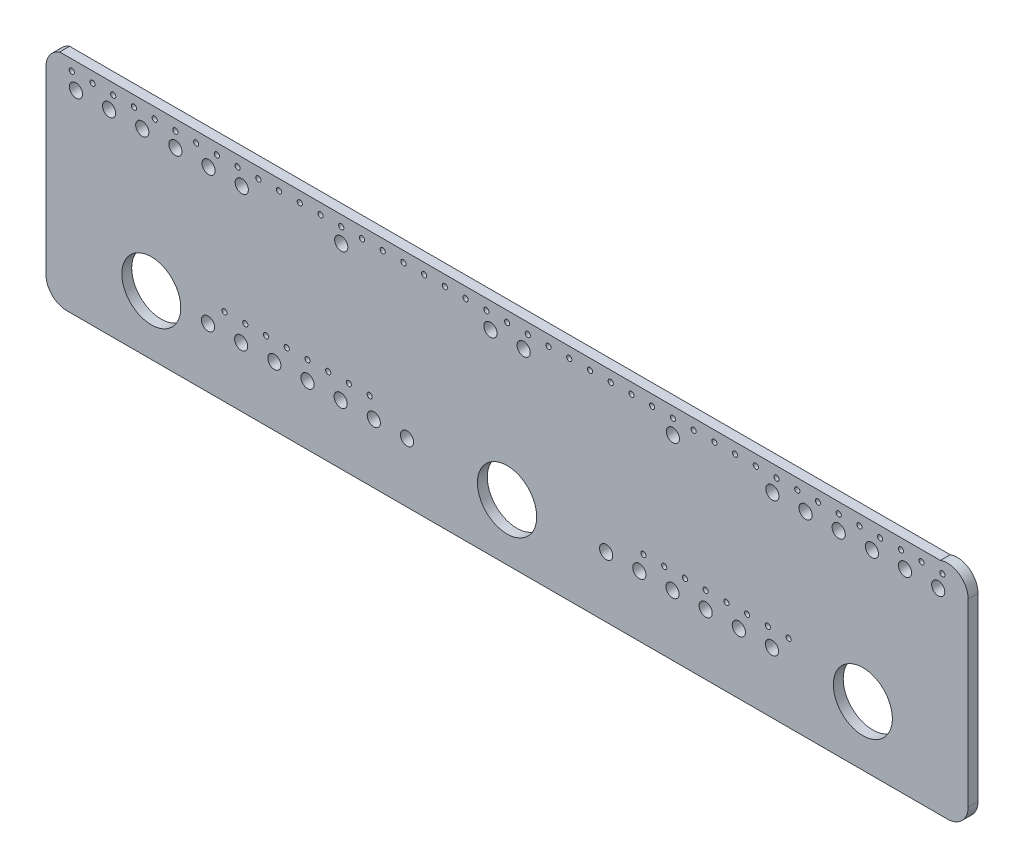
SolidWorks part; units mm, degrees
ref_plane "Front" through (0, 0, 0) normal (0, 0, 1) x (1, 0, 0)
ref_plane "Top" through (0, 0, 0) normal (0, 1, 0) x (1, 0, 0)
ref_plane "Right" through (0, 0, 0) normal (1, 0, 0) x (0, 0, -1)
sketch "Sketch1" plane through (0, 0, 0) normal (0, 0, 1) x (1, 0, 0)
  line L0 (-438.5452, 90.4904) -> (-13.6652, 90.4904)
  line L2 (-445.1498, 81.0845) -> (-445.1498, -5.9096)
  line L4 (-0.2698, 81.0845) -> (-0.2698, -5.9096)
  line L5 (-10.2698, -15.9096) -> (-435.1498, -15.9096)
  circle A0 centre (-394.3498, 12.7904) radius 14.225
  circle A1 centre (-51.0698, 12.7904) radius 14.225
  circle A11 centre (-222.7098, 11.2904) radius 14.3
  arc A26 (-438.5452, 90.4904) -> (-445.1498, 81.0845) centre (-435.1498, 81.0845) ccw
  arc A27 (-13.6652, 90.4904) -> (-0.2698, 81.0845) centre (-10.2698, 81.0845) cw
  circle A54 centre (-174.8998, 13.3845) radius 3.18
  circle A151 centre (-366.9908, 12.7904) radius 3.18
  circle A155 centre (-358.9957, 21.7191) radius 1.25
  circle A159 centre (-94.8998, 13.3845) radius 3.18
  circle A279 centre (-96.8998, 21.3845) radius 1.25
  circle A285 centre (-106.8998, 21.3845) radius 1.25
  circle A286 centre (-350.9908, 12.7904) radius 3.18
  circle A288 centre (-334.9908, 12.7904) radius 3.18
  circle A290 centre (-318.9908, 12.7904) radius 3.18
  circle A292 centre (-302.9908, 12.7904) radius 3.18
  circle A294 centre (-286.9908, 12.7904) radius 3.18
  circle A296 centre (-158.8998, 13.3845) radius 3.18
  circle A297 centre (-142.8998, 13.3845) radius 3.18
  circle A298 centre (-126.8998, 13.3845) radius 3.18
  circle A299 centre (-110.8998, 13.3845) radius 3.18
  circle A309 centre (-86.8998, 21.3845) radius 1.25
  circle A314 centre (-270.9908, 12.7904) radius 3.18
  circle A328 centre (-348.9957, 21.7191) radius 1.25
  circle A361 centre (-116.8998, 21.3845) radius 1.25
  circle A362 centre (-338.9957, 21.7191) radius 1.25
  circle A363 centre (-328.9957, 21.7191) radius 1.25
  circle A364 centre (-318.9957, 21.7191) radius 1.25
  circle A365 centre (-308.9957, 21.7191) radius 1.25
  circle A366 centre (-298.9957, 21.7191) radius 1.25
  circle A367 centre (-288.9957, 21.7191) radius 1.25
  circle A378 centre (-126.8998, 21.3845) radius 1.25
  circle A379 centre (-136.8998, 21.3845) radius 1.25
  circle A380 centre (-146.8998, 21.3845) radius 1.25
  circle A381 centre (-156.8998, 21.3845) radius 1.25
  circle A402 centre (-222.7098, 85.3845) radius 1.25
  circle A438 centre (-142.7098, 78.3345) radius 3.18
  circle A439 centre (-94.7098, 78.3345) radius 3.18
  circle A440 centre (-78.7098, 78.3345) radius 3.18
  circle A441 centre (-30.7098, 78.3345) radius 3.18
  circle A442 centre (-14.7098, 78.3345) radius 3.18
  circle A444 centre (-302.7098, 78.3345) radius 3.18
  circle A445 centre (-350.7098, 78.3345) radius 3.18
  circle A446 centre (-366.7098, 78.3345) radius 3.18
  circle A447 centre (-414.7098, 78.3345) radius 3.18
  circle A448 centre (-212.7098, 85.3845) radius 1.25
  circle A449 centre (-202.7098, 85.3845) radius 1.25
  circle A450 centre (-192.7098, 85.3845) radius 1.25
  circle A451 centre (-182.7098, 85.3845) radius 1.25
  circle A452 centre (-172.7098, 85.3845) radius 1.25
  circle A453 centre (-162.7098, 85.3845) radius 1.25
  circle A454 centre (-152.7098, 85.3845) radius 1.25
  circle A455 centre (-142.7098, 85.3845) radius 1.25
  circle A456 centre (-132.7098, 85.3845) radius 1.25
  circle A457 centre (-122.7098, 85.3845) radius 1.25
  circle A458 centre (-112.7098, 85.3845) radius 1.25
  circle A459 centre (-102.7098, 85.3845) radius 1.25
  circle A460 centre (-92.7098, 85.3845) radius 1.25
  circle A461 centre (-82.7098, 85.3845) radius 1.25
  circle A462 centre (-72.7098, 85.3845) radius 1.25
  circle A463 centre (-62.7098, 85.3845) radius 1.25
  circle A464 centre (-52.7098, 85.3845) radius 1.25
  circle A465 centre (-42.7098, 85.3845) radius 1.25
  circle A466 centre (-32.7098, 85.3845) radius 1.25
  circle A467 centre (-22.7098, 85.3845) radius 1.25
  circle A468 centre (-12.7098, 85.3845) radius 1.25
  circle A469 centre (-232.7098, 85.3845) radius 1.25
  circle A470 centre (-242.7098, 85.3845) radius 1.25
  circle A471 centre (-252.7098, 85.3845) radius 1.25
  circle A472 centre (-262.7098, 85.3845) radius 1.25
  circle A473 centre (-272.7098, 85.3845) radius 1.25
  circle A474 centre (-282.7098, 85.3845) radius 1.25
  circle A475 centre (-292.7098, 85.3845) radius 1.25
  circle A476 centre (-302.7098, 85.3845) radius 1.25
  circle A477 centre (-312.7098, 85.3845) radius 1.25
  circle A478 centre (-322.7098, 85.3845) radius 1.25
  circle A479 centre (-332.7098, 85.3845) radius 1.25
  circle A480 centre (-342.7098, 85.3845) radius 1.25
  circle A481 centre (-352.7098, 85.3845) radius 1.25
  circle A482 centre (-362.7098, 85.3845) radius 1.25
  circle A483 centre (-372.7098, 85.3845) radius 1.25
  circle A484 centre (-382.7098, 85.3845) radius 1.25
  circle A485 centre (-392.7098, 85.3845) radius 1.25
  circle A486 centre (-402.7098, 85.3845) radius 1.25
  circle A487 centre (-412.7098, 85.3845) radius 1.25
  circle A488 centre (-422.7098, 85.3845) radius 1.25
  circle A489 centre (-432.7098, 85.3845) radius 1.25
  circle A512 centre (-430.7098, 78.3345) radius 3.18
  circle A513 centre (-230.7098, 78.3345) radius 3.18
  circle A514 centre (-214.7098, 78.3345) radius 3.18
  circle A526 centre (-398.7098, 78.3345) radius 3.18
  circle A527 centre (-382.7098, 78.3345) radius 3.18
  circle A536 centre (-350.7098, 46.3345) radius 3.18 [skipped]
  circle A537 centre (-366.7098, 46.3345) radius 3.18 [skipped]
  circle A538 centre (-350.7098, 62.3345) radius 3.18 [skipped]
  circle A539 centre (-366.7098, 62.3345) radius 3.18 [skipped]
  circle A540 centre (-382.7098, 62.3345) radius 3.18 [skipped]
  circle A541 centre (-398.7098, 62.3345) radius 3.18 [skipped]
  circle A542 centre (-46.7098, 78.3345) radius 3.18
  circle A543 centre (-62.7098, 78.3345) radius 3.18
  circle A552 centre (-94.7098, 46.3345) radius 3.18 [skipped]
  circle A553 centre (-78.7098, 46.3345) radius 3.18 [skipped]
  circle A554 centre (-78.7098, 62.3345) radius 3.18 [skipped]
  circle A555 centre (-94.7098, 62.3345) radius 3.18 [skipped]
  circle A556 centre (-46.7098, 62.3345) radius 3.18 [skipped]
  circle A557 centre (-62.7098, 62.3345) radius 3.18 [skipped]
  circle A597 centre (-278.9957, 21.7191) radius 1.25 [skipped]
  circle A598 centre (-166.8998, 21.3845) radius 1.25 [skipped]
  circle A601 centre (-86.8998, 1.3845) radius 1.25 [skipped]
  circle A602 centre (-96.8998, 1.3845) radius 1.25 [skipped]
  circle A603 centre (-116.8998, 1.3845) radius 1.25 [skipped]
  circle A604 centre (-106.8998, 1.3845) radius 1.25 [skipped]
  circle A605 centre (-126.8998, 1.3845) radius 1.25 [skipped]
  circle A606 centre (-136.8998, 1.3845) radius 1.25 [skipped]
  circle A607 centre (-146.8998, 1.3845) radius 1.25 [skipped]
  circle A608 centre (-156.8998, 1.3845) radius 1.25 [skipped]
  circle A609 centre (-166.8998, 1.3845) radius 1.25 [skipped]
  circle A610 centre (-278.9957, 1.7191) radius 1.25 [skipped]
  circle A611 centre (-288.9957, 1.7191) radius 1.25 [skipped]
  circle A612 centre (-298.9957, 1.7191) radius 1.25 [skipped]
  circle A613 centre (-308.9957, 1.7191) radius 1.25 [skipped]
  circle A614 centre (-318.9957, 1.7191) radius 1.25 [skipped]
  circle A615 centre (-328.9957, 1.7191) radius 1.25 [skipped]
  circle A616 centre (-338.9957, 1.7191) radius 1.25 [skipped]
  circle A617 centre (-348.9957, 1.7191) radius 1.25 [skipped]
  circle A618 centre (-358.9957, 1.7191) radius 1.25 [skipped]
  arc A619 (-10.2698, -15.9096) -> (-0.2698, -5.9096) centre (-10.2698, -5.9096) ccw
  arc A620 (-435.1498, -15.9096) -> (-445.1498, -5.9096) centre (-435.1498, -5.9096) cw
  circle A625 centre (-398.7098, 46.3345) radius 3.18 [skipped]
  circle A626 centre (-382.7098, 46.3345) radius 3.18 [skipped]
  circle A632 centre (-62.7098, 46.3345) radius 3.18 [skipped]
  circle A633 centre (-46.7098, 46.3345) radius 3.18 [skipped]
  point P45 (-0.2698, -21.5096)
  point P52 (-0.2698, 90.4904)
  dimension "D2" = 50.8
  dimension "D4" = 50.8
  dimension "D6" = 222.44
  dimension "D12" = 171.64
  dimension "D13" = 22
  dimension "D14" = 10
  dimension "D16" = 2
  dimension "D21" = 2
  dimension "D23" = 3
  dimension "D29" = 10
  dimension "D30" = 10
  dimension "D24" = 2
  dimension "D25" = 171.64
  dimension "D40" = 10
  dimension "D1" = 112
  dimension "D7" = 6
  dimension "D9" = 5
  dimension "D11" = 22
  dimension "D19" = 2
  dimension "D20" = 9
  dimension "D22" = 2
  dimension "D31" = 3
extrude "Boss-Extrude5" add sketch "Sketch1" along normal blind 4.7625
move or copy body "Body-Move/Copy1" [suppressed]
